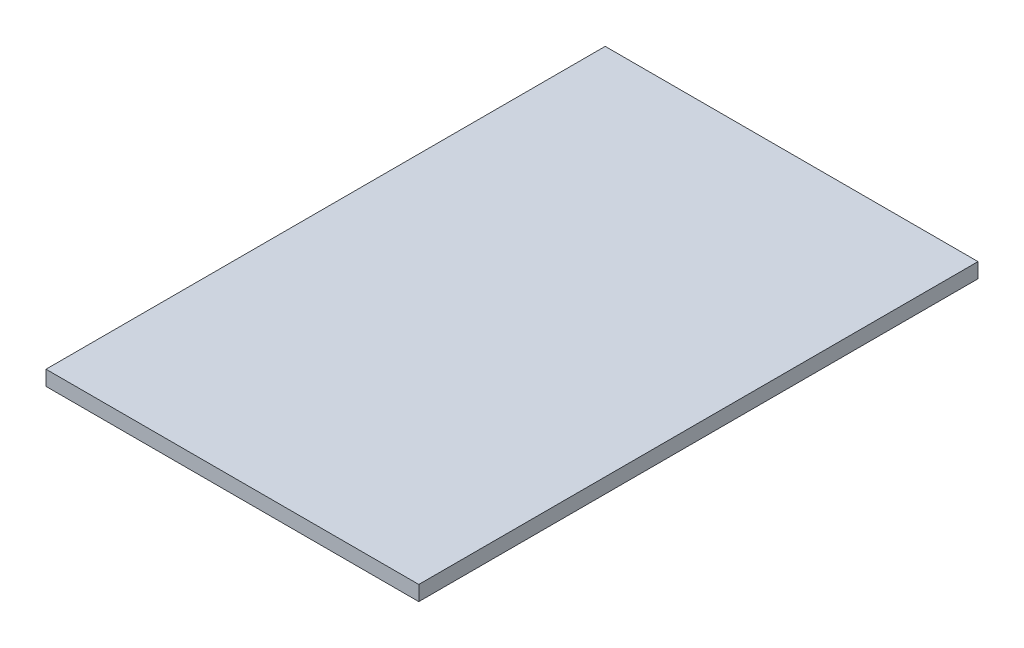
SolidWorks part; units mm, degrees
ref_plane "Front Plane" through (0, 0, 0) normal (0, 0, 1) x (1, 0, 0)
ref_plane "Top Plane" through (0, 0, 0) normal (0, 1, 0) x (1, 0, 0)
ref_plane "Right Plane" through (0, 0, 0) normal (1, 0, 0) x (0, 0, -1)
sketch "Sketch2" plane through (0, 0, 0) normal (0, 1, 0) x (1, 0, 0)
  line L0 (0, 0) -> (100, 0)
  line L1 (0, 0) -> (0, -150)
  line L2 (100, 0) -> (100, -150)
  line L3 (0, -150) -> (100, -150)
  dimension "D1" = 100
  dimension "D2" = 150
extrude "Boss-Extrude1" add sketch "Sketch2" along normal blind 4
